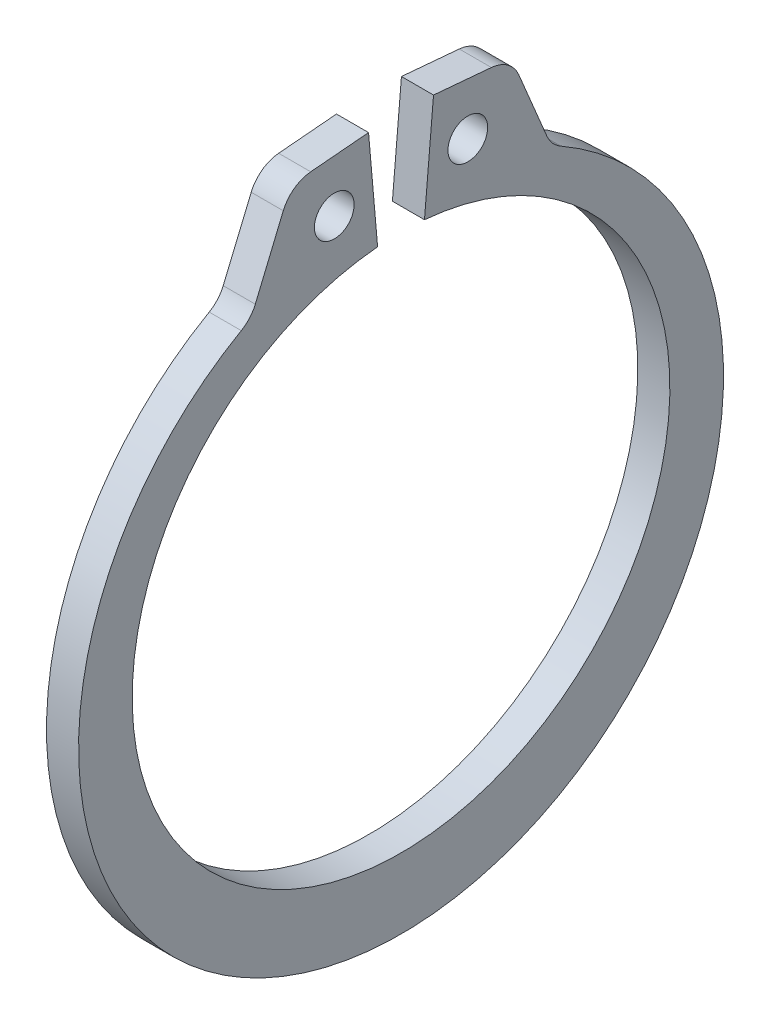
SolidWorks part; units mm, degrees
material "Cast Carbon Steel"
ref_plane "Front" through (0, 0, 0) normal (0, 0, 1) x (1, 0, 0)
ref_plane "Top" through (0, 0, 0) normal (0, 1, 0) x (1, 0, 0)
ref_plane "Right" through (0, 0, 0) normal (1, 0, 0) x (0, 0, -1)
sketch "Sketch1" plane through (0, 0, 0) normal (1, 0, 0) x (0, 0, -1)
  line L0 (0, 0) -> (0, 8.9408) construction
  line L1 (-0.7792, 8.9068) -> (-1.0803, 12.348)
  line L2 (1.0803, 12.348) -> (3.6613, 12.1222)
  line L3 (3.6613, 12.1222) -> (4.994, 8.9353)
  line L4 (0.7792, 8.9068) -> (1.0803, 12.348)
  line L5 (-1.0803, 12.348) -> (-3.6613, 12.1222)
  line L6 (-3.6613, 12.1222) -> (-4.994, 8.9353)
  line L7 (-4.994, 8.9353) -> (-4.362, 7.8045) construction
  line L8 (4.994, 8.9353) -> (4.362, 7.8045) construction
  line L9 (0, -8.9408) -> (0, -11.2776) construction
  line L10 (-3.6613, 12.1222) -> (-0.7792, 8.9068) construction
  line L11 (0, 8.9408) -> (0, 12.3952) construction
  line L12 (-8.9408, 0) -> (8.9408, 0) construction
  circle A0 centre (0, 0) radius 8.9408 construction
  arc A1 (-0.7792, 8.9068) -> (0.7792, 8.9068) centre (0, 0) ccw
  circle A3 centre (0, 0) radius 13.335 construction
  circle A4 centre (-2.2202, 10.5145) radius 0.6604
  circle A5 centre (2.2202, 10.5145) radius 0.6604
  arc A6 (-4.994, 8.9353) -> (4.994, 8.9353) centre (0, -0.5542) ccw
  point P0 (0, -11.2776)
  dimension "A" = 17.8816
  dimension "Hole" = 1.3208
  dimension "Smin" = 1.2954
  dimension "H" = 3.4544
  dimension "D2" = 2.5908
  dimension "Angle" = 5
extrude "Extrude1" add sketch "Sketch1" along normal mid plane 1.0668
fillet "Fillet1" radius 1.0922 4 edges at (0, 8.9353, 4.994) (0, 8.9353, -4.994) (0, 12.1222, 3.6613) (0, 12.1222, -3.6613)
sketch "Sketch2" plane through (0, 0, 0) normal (0, 0, 1) x (1, 0, 0)
  line L0 (-5.9182, 0) -> (15.4178, 0)
  line L1 (15.4178, 0) -> (15.4178, -9.525)
  line L2 (-0.5842, -9.525) -> (-5.334, -9.525)
  line L3 (15.4178, -9.525) -> (0.5842, -9.525)
  line L4 (0.5842, -9.525) -> (0.5842, -8.9408)
  line L5 (0.5842, -8.9408) -> (-0.5842, -8.9408)
  line L6 (-0.5842, -8.9408) -> (-0.5842, -9.525)
  line L7 (-0.5842, -9.525) -> (-5.9182, -9.525) construction
  line L8 (-5.9182, -9.525) -> (-5.9182, 0) construction
  line L9 (15.4178, 0) -> (76.391, 0) construction
  line L10 (-5.334, -9.525) -> (-5.9182, -8.9408)
  line L11 (-5.9182, -8.9408) -> (-5.9182, 0)
  point P10 (0, -8.9408)
  dimension "D2" = 21.336
  dimension "D3" = 5.334
  dimension "D1" = 45
revolve "Revolve1" [suppressed] add sketch "Sketch2" angle 360 about L9
delete or keep bodies "Body-Delete1" [suppressed] type delete bodies bodies 122
equation "\"D2@Sketch2\" = \"D1@Extrude1\"*20"
equation "\"D3@Sketch2\" = \"D2@Sketch2\"/4"
equation "\"D2@Sketch1\" = \"H@Sketch1\"*.75"
